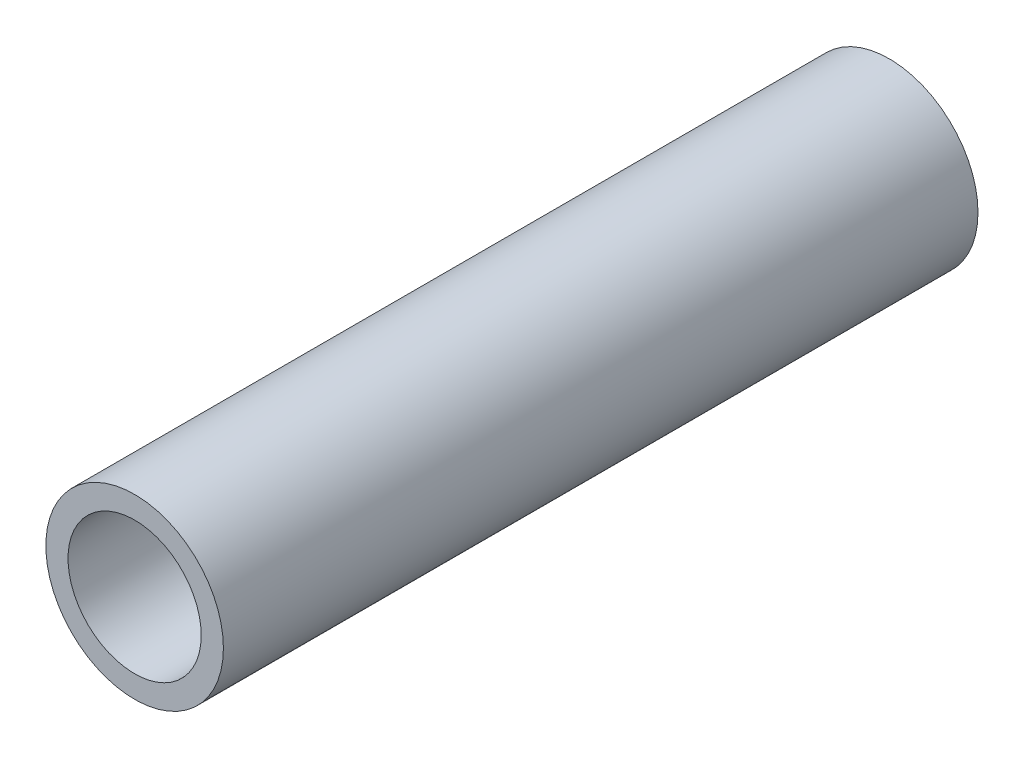
SolidWorks part; units mm, degrees
ref_plane "前视基准面" through (0, 0, 0) normal (0, 0, 1) x (1, 0, 0)
ref_plane "上视基准面" through (0, 0, 0) normal (0, 1, 0) x (1, 0, 0)
ref_plane "右视基准面" through (0, 0, 0) normal (1, 0, 0) x (0, 0, -1)
sketch "草图1" plane through (0, 0, 0) normal (0, 0, 1) x (1, 0, 0)
  circle A0 centre (0, 0) radius 2
  circle A1 centre (0, 0) radius 1.5
extrude "凸台-拉伸1" add sketch "草图1" along normal blind 17
